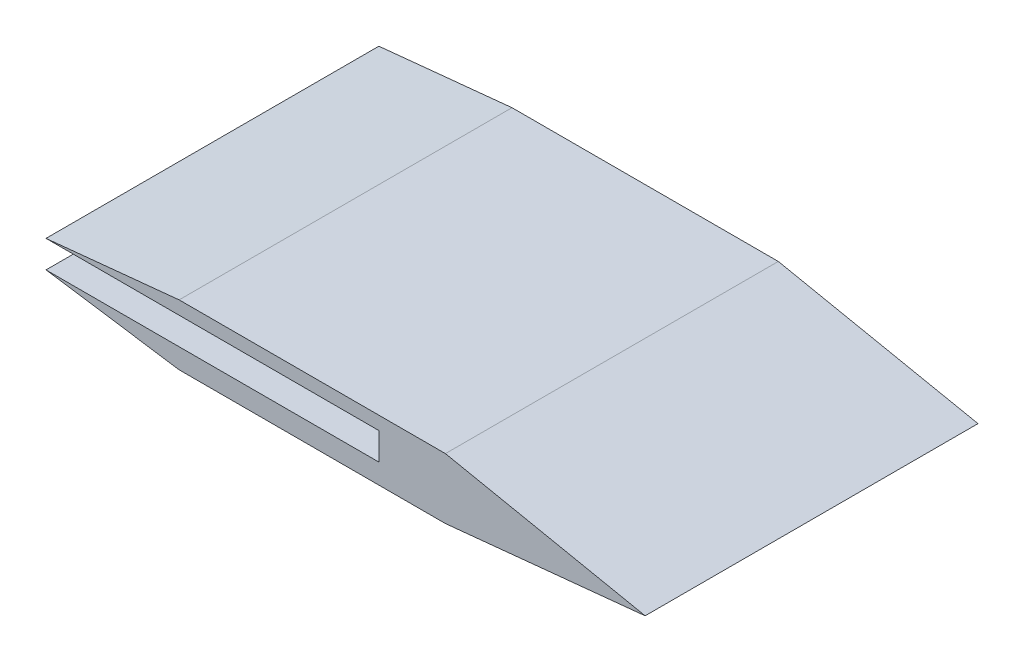
SolidWorks part; units mm, degrees
ref_plane "Přední rovina" through (0, 0, 0) normal (0, 0, 1) x (1, 0, 0)
ref_plane "Horní rovina" through (0, 0, 0) normal (0, 1, 0) x (1, 0, 0)
ref_plane "Pravá rovina" through (0, 0, 0) normal (1, 0, 0) x (0, 0, -1)
sketch "Skica1" plane through (0, 0, 0) normal (0, 0, 1) x (1, 0, 0)
  line L0 (0, 0) -> (20, 2)
  line L1 (20, 2) -> (60, 2)
  line L2 (60, 2) -> (90, -4.1)
  line L3 (90, -4.1) -> (60, -7.1)
  line L6 (0, -4.1) -> (50, -4.1)
  line L7 (50, -4.1) -> (50, 0)
  line L8 (50, 0) -> (0, 0)
  line L9 (50, -4.1) -> (113.4883, -4.1) construction
  line L10 (60, -7.1) -> (20, -7.1)
  line L11 (20, -7.1) -> (0, -4.1)
  point P3 (92.0016, -3.1)
  point P11 (55.2998, -5.6)
  point P12 (93.5979, -3.1)
  point P13 (0, 0)
  point P14 (79.6604, -3.1)
  point P15 (80, -3.1)
  point P16 (95.1476, -3.1)
  dimension "D1" = 4.1
  dimension "D2" = 3
  dimension "D3" = 2
  dimension "D4" = 20
  dimension "D5" = 20
  dimension "D6" = 50
  dimension "D7" = 50
  dimension "D8" = 40
  dimension "D9" = 40
extrude "Přidat vysunutím1" add sketch "Skica1" along normal blind 50
